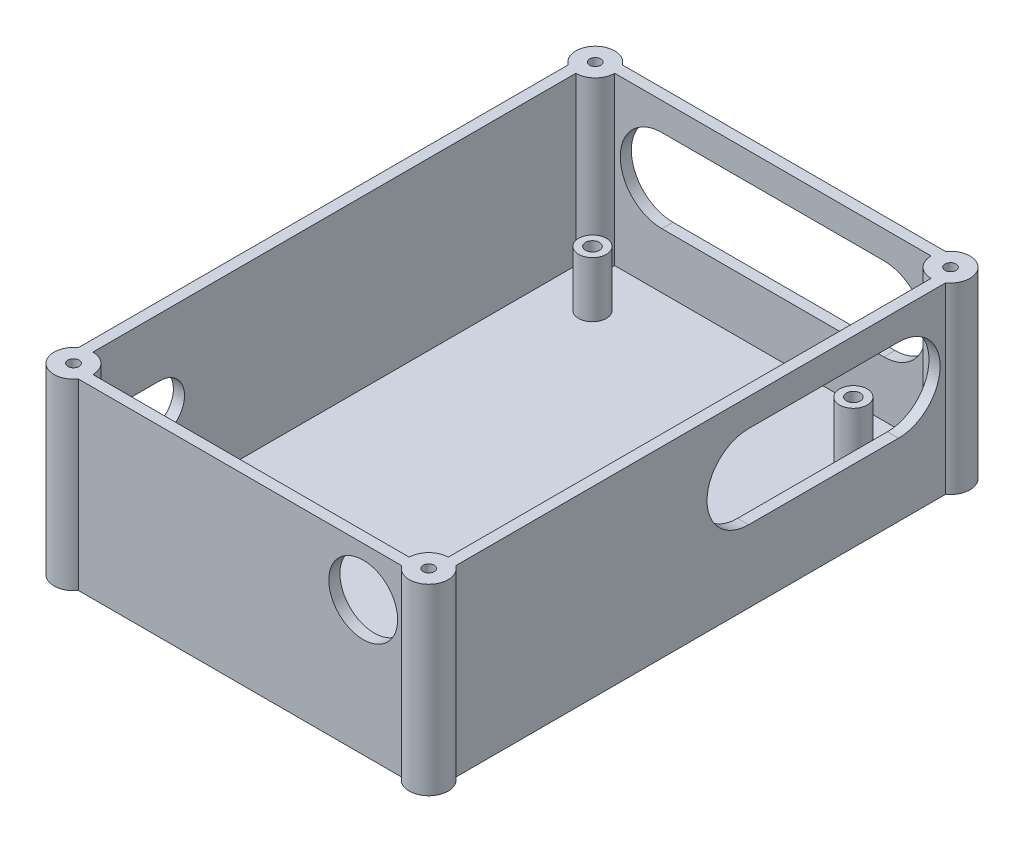
SolidWorks part; units mm, degrees
ref_plane "Front Plane" through (0, 0, 0) normal (0, 0, 1) x (1, 0, 0)
ref_plane "Top Plane" through (0, 0, 0) normal (0, 1, 0) x (1, 0, 0)
ref_plane "Right Plane" through (0, 0, 0) normal (1, 0, 0) x (0, 0, -1)
sketch "Sketch1" plane through (0, 0, 0) normal (0, 1, 0) x (1, 0, 0)
  line L0 (-22.672, -40.5) -> (-22.672, -43.5)
  line L1 (-28.172, 43.5) -> (29.828, 43.5)
  line L2 (-28.172, 43.5) -> (-28.172, -43.5)
  line L3 (-28.172, -43.5) -> (29.828, -43.5)
  line L4 (29.828, 43.5) -> (29.828, -43.5)
  line L5 (-25.172, -38) -> (-28.172, -38)
  line L6 (0.828, -43.5) -> (0.828, 43.5) construction
  line L7 (-28.172, 0) -> (29.828, 0) construction
  line L8 (33.828, 47.5) -> (33.828, -47.5)
  line L9 (-32.172, -47.5) -> (33.828, -47.5)
  line L10 (-32.172, 47.5) -> (-32.172, -47.5)
  line L11 (-32.172, 47.5) -> (33.828, 47.5)
  circle A0 centre (-22.672, -38) radius 2.5
  circle A1 centre (-22.672, -38) radius 1.25
  circle A2 centre (24.328, -38) radius 2.5
  circle A3 centre (24.328, -38) radius 1.25
  circle A4 centre (24.328, 38) radius 1.25
  circle A5 centre (24.328, 38) radius 2.5
  circle A6 centre (-22.672, 38) radius 2.5
  circle A7 centre (-22.672, 38) radius 1.25
  point P0 (0, 0)
  dimension "D5" = 5
  dimension "D6" = 2.5
  dimension "D1" = 87
  dimension "D2" = 58
  dimension "D3" = 3
  dimension "D4" = 3
  dimension "D7" = 4
extrude "Boss-Extrude1" add sketch "Sketch1" along normal blind 10 contours A2 A3 | A5 A4 | A6 A7 | A0 A1
sketch "Sketch2" plane through (0, 0, 0) normal (0, 1, 0) x (1, 0, 0)
  line L0 (-22.672, -38) -> (24.328, -38)
  line L1 (0.828, -38) -> (0.828, 0)
  line L3 (-33.172, 49) -> (34.828, 49)
  line L4 (-33.172, 49) -> (-33.172, -49)
  line L5 (-33.172, -49) -> (34.828, -49)
  line L6 (34.828, 49) -> (34.828, -49)
  line L7 (-33.172, 49) -> (34.828, -49) construction
  line L8 (-33.172, -49) -> (34.828, 49) construction
  dimension "D1" = 68
  dimension "D2" = 98
extrude "Boss-Extrude2" add sketch "Sketch2" against normal blind 3
sketch "Sketch3" plane through (0, 0, 0) normal (0, 1, 0) x (1, 0, 0)
  line L4 (-33.172, -49) -> (34.828, -49)
  line L5 (34.828, -49) -> (34.828, 49)
  line L6 (34.828, 49) -> (-33.172, 49)
  line L7 (-33.172, 49) -> (-33.172, -49)
  line L8 (32.828, -47) -> (32.828, 47)
  line L9 (32.828, 47) -> (-31.172, 47)
  line L10 (-31.172, 47) -> (-31.172, -47)
  line L11 (-31.172, -47) -> (32.828, -47)
  line L12 (32.828, -47) -> (32.828, 47)
  line L13 (32.828, 47) -> (-31.172, 47)
  line L14 (-31.172, 47) -> (-31.172, -47)
  line L15 (-31.172, -47) -> (32.828, -47)
  dimension "D1" = 2
  dimension "D2" = 2
extrude "Boss-Extrude3" add sketch "Sketch3" along normal blind 30 contours L4 L5 L6 L7 | L12 L13 L14 L15
sketch "Sketch4" plane through (0, 0, 49) normal (0, 0, 1) x (1, 0, 0)
  line L0 (23.028, 15) -> (23.028, -3)
  line L1 (-33.172, -3) -> (34.828, -3) construction
  line L2 (23.028, 21.2) -> (34.828, 21.2)
  line L3 (34.828, -3) -> (34.828, 30) construction
  circle A0 centre (23.028, 21.2) radius 6.2
  dimension "D1" = 12.4
  dimension "D2" = 18
  dimension "D3" = 11.8
extrude "Cut-Extrude1" cut sketch "Sketch4" against normal blind 25
sketch "Sketch5" plane through (-33.172, 0, 0) normal (-1, 0, 0) x (0, 0, 1)
  line L0 (31.5, 15) -> (42.5, 15) construction
  line L1 (31.5, 19.5) -> (42.5, 19.5)
  line L2 (31.5, 10.5) -> (42.5, 10.5)
  line L3 (37, -3) -> (37, 15)
  line L4 (-49, -3) -> (49, -3) construction
  line L5 (47, 15) -> (27, 15)
  line L6 (49, -3) -> (49, 30) construction
  arc A0 (31.5, 19.5) -> (31.5, 10.5) centre (31.5, 15) ccw
  arc A1 (42.5, 10.5) -> (42.5, 19.5) centre (42.5, 15) ccw
  point P2 (37, 15)
  dimension "D1" = 18
  dimension "D2" = 9
  dimension "D3" = 20
  dimension "D4" = 12
extrude "Cut-Extrude2" cut sketch "Sketch5" against normal blind 5 contours L5 A1 L1 A0 | L5 A0 L2 L3 | L2 A1 L5 L3
sketch "Sketch7" plane through (0, 30, 0) normal (0, 1, 0) x (1, 0, 0)
  circle A0 centre (32.828, -47) radius 3.5
  circle A1 centre (32.828, 47) radius 3.5
  circle A2 centre (-31.172, 47) radius 3.5
  circle A3 centre (-31.172, -47) radius 3.5
  dimension "D1" = 7
extrude "Boss-Extrude5" add sketch "Sketch7" against normal blind 33
sketch "Sketch8" plane through (0, 30, 0) normal (0, 1, 0) x (1, 0, 0)
  circle A0 centre (-31.172, -47) radius 1
  circle A1 centre (32.828, -47) radius 1
  circle A2 centre (32.828, 47) radius 1
  circle A3 centre (-31.172, 47) radius 1
  dimension "D1" = 2
extrude "Cut-Extrude3" cut sketch "Sketch8" against normal blind 7
sketch "Sketch9" plane through (0, 30, 0) normal (0, 1, 0) x (1, 0, 0)
  line L1 (34.3743, -49.5734) -> (35.8298, -46.9475)
  line L2 (35.8298, -46.9475) -> (34.2835, -44.3742)
  line L3 (34.2835, -44.3742) -> (31.2817, -44.4266)
  line L4 (31.2817, -44.4266) -> (29.8262, -47.0525)
  line L5 (29.8262, -47.0525) -> (31.3726, -49.6258)
  line L6 (31.3726, -49.6258) -> (34.3743, -49.5734)
  line L7 (34.3035, 44.3854) -> (35.8301, 46.9705)
  line L8 (35.8301, 46.9705) -> (34.3546, 49.5851)
  line L9 (34.3546, 49.5851) -> (31.3525, 49.6146)
  line L10 (31.3525, 49.6146) -> (29.8259, 47.0295)
  line L11 (29.8259, 47.0295) -> (31.3014, 44.4149)
  line L12 (31.3014, 44.4149) -> (34.3035, 44.3854)
  line L13 (-29.6071, 44.4379) -> (-28.1707, 47.0741)
  line L14 (-28.1707, 47.0741) -> (-29.7355, 49.6363)
  line L15 (-29.7355, 49.6363) -> (-32.7368, 49.5621)
  line L16 (-32.7368, 49.5621) -> (-34.1733, 46.9259)
  line L17 (-34.1733, 46.9259) -> (-32.6085, 44.3637)
  line L18 (-32.6085, 44.3637) -> (-29.6071, 44.4379)
  line L19 (-29.6404, -49.5822) -> (-28.17, -46.9647)
  line L20 (-28.17, -46.9647) -> (-29.7015, -44.3825)
  line L21 (-29.7015, -44.3825) -> (-32.7035, -44.4178)
  line L22 (-32.7035, -44.4178) -> (-34.174, -47.0353)
  line L23 (-34.174, -47.0353) -> (-32.6424, -49.6175)
  line L24 (-32.6424, -49.6175) -> (-29.6404, -49.5822)
  circle A0 centre (32.828, -47) radius 2.6 construction
  circle A1 centre (32.828, 47) radius 2.6 construction
  circle A2 centre (-31.172, 47) radius 2.6 construction
  circle A3 centre (-31.172, -47) radius 2.6 construction
  dimension "D1" = 5.2
  dimension "D2" = 5.2
extrude "Cut-Extrude4" [suppressed] cut sketch "Sketch9" against normal blind 3.5
sketch "Sketch12" plane through (0, 0, -49) normal (0, 0, -1) x (-1, 0, 0)
  line L0 (-20.828, 17.5) -> (19.172, 17.5) construction
  line L1 (-20.828, 25) -> (19.172, 25)
  line L2 (-20.828, 10) -> (19.172, 10)
  line L3 (-29.9557, 30) -> (28.2997, 30) construction
  line L4 (-0.828, 30) -> (-0.828, 25)
  arc A0 (-20.828, 25) -> (-20.828, 10) centre (-20.828, 17.5) ccw
  arc A1 (19.172, 10) -> (19.172, 25) centre (19.172, 17.5) ccw
  point P2 (-0.828, 17.5)
  point P7 (-0.828, 30)
  point P8 (-0.828, 25)
  dimension "D1" = 15
  dimension "D2" = 40
  dimension "D3" = 5
extrude "Cut-Extrude6" cut sketch "Sketch12" against normal blind 3.3
sketch "Sketch13" plane through (0, 30, 0) normal (0, 1, 0) x (1, 0, 0)
  line L0 (-31.172, 47) -> (32.828, 47)
  line L1 (32.828, 47) -> (32.828, -47)
sketch "Sketch14" plane through (34.828, 0, 0) normal (1, 0, 0) x (0, 0, -1)
  line L0 (8.6339, 17.5) -> (35.6216, 17.5) construction
  line L1 (8.6339, 25) -> (35.6216, 25)
  line L2 (8.6339, 10) -> (35.6216, 10)
  line L3 (47, 30) -> (-47, 30) construction
  line L4 (44.1277, -3) -> (44.1277, 30) construction
  arc A0 (8.6339, 25) -> (8.6339, 10) centre (8.6339, 17.5) ccw
  arc A1 (35.6216, 10) -> (35.6216, 25) centre (35.6216, 17.5) ccw
  point P2 (22.1277, 17.5)
  dimension "D1" = 15
  dimension "D2" = 5
  dimension "D3" = 22
extrude "Cut-Extrude7" cut sketch "Sketch14" against normal blind 10
